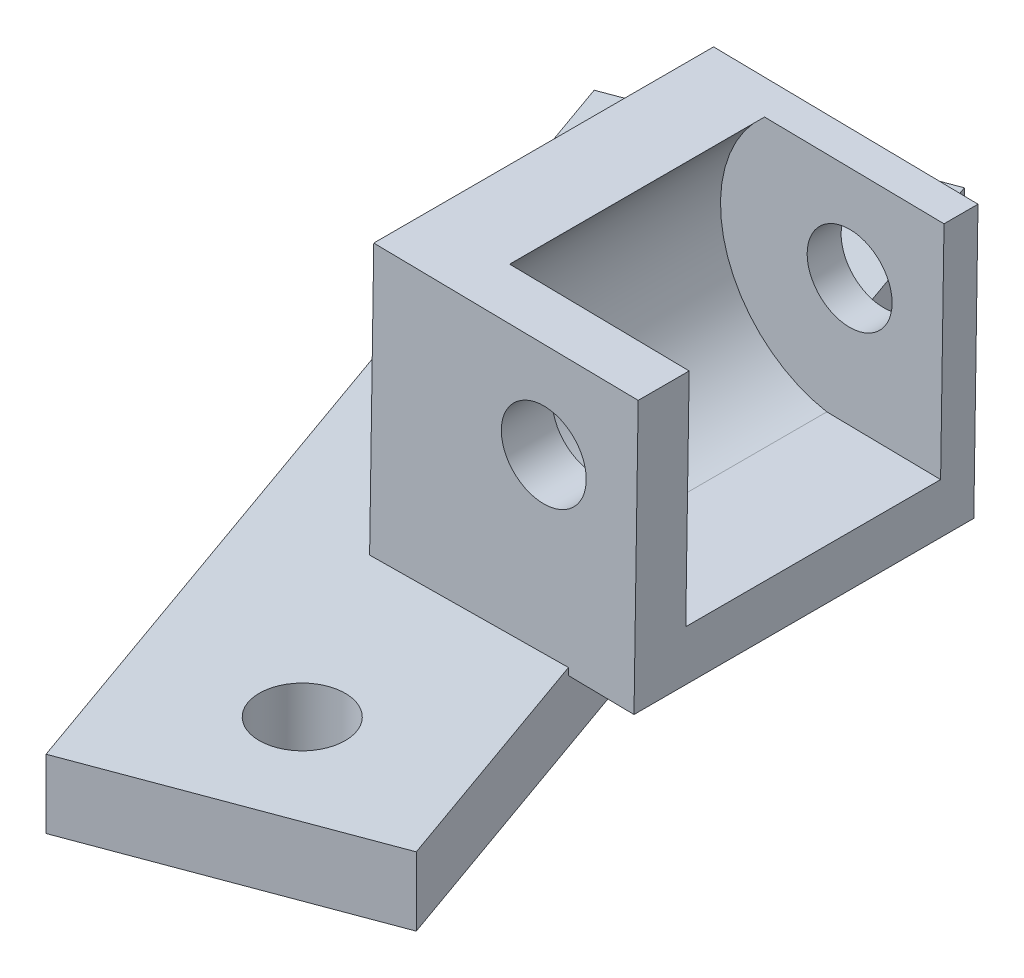
SolidWorks part; units mm, degrees
ref_plane "Front Plane" through (0, 0, 0) normal (0, 0, 1) x (1, 0, 0)
ref_plane "Top Plane" through (0, 0, 0) normal (0, 1, 0) x (1, 0, 0)
ref_plane "Right Plane" through (0, 0, 0) normal (1, 0, 0) x (0, 0, -1)
sketch "Sketch1" plane through (0, 0, 0) normal (0, 0, 1) x (1, 0, 0)
  line L0 (-620.8374, 110.7203) -> (-621.1503, 90.2249)
  line L1 (-604.7125, 110.4741) -> (-634.2525, 110.9251) construction
  line L2 (-621.1503, 90.2249) -> (-640.9147, 90.5267)
  line L3 (-640.9147, 90.5267) -> (-640.6018, 111.0221)
  line L4 (-640.6018, 111.0221) -> (-620.8374, 110.7203)
  line L5 (-606.4491, 93.8109) -> (-629.5989, 94.1643) construction
  line L6 (-606.4491, 93.8109) -> (-629.5989, 94.1643)
  arc A0 (-634.2525, 110.9251) -> (-634.4712, 96.6012) centre (-627.8931, 103.6644) ccw construction
  arc A1 (-634.4712, 96.6012) -> (-629.5989, 94.1643) centre (-627.8931, 103.6644) ccw construction
  arc A2 (-634.2525, 110.9251) -> (-634.4712, 96.6012) centre (-627.8931, 103.6644) ccw
  arc A3 (-634.4712, 96.6012) -> (-629.5989, 94.1643) centre (-627.8931, 103.6644) ccw
  dimension "D1" = 3.81
  dimension "D2" = 6.35
  dimension "D3" = 19.7667
extrude "Boss-Extrude1" add sketch "Sketch1" against normal blind 21.59 contours A3 A2 L4 L3 L2 L0 L6
sketch "Sketch2" plane through (0, 0, -19.05) normal (0, 0, -1) x (-1, 0, 0)
  line L0 (621.0921, 94.0345) -> (620.8374, 110.7203)
  line L1 (604.6203, 110.4727) -> (634.2525, 110.9251) construction
  line L2 (620.8374, 110.7203) -> (634.2525, 110.9251)
  line L3 (621.0921, 94.0345) -> (629.5989, 94.1643) construction
  line L4 (621.0921, 94.0345) -> (629.5989, 94.1643)
  line L5 (621.0921, 94.0345) -> (629.5989, 94.1643)
  circle A0 centre (627.8931, 103.6644) radius 3.175 construction
  arc A1 (629.5989, 94.1643) -> (634.2525, 110.9251) centre (627.8931, 103.6644) ccw construction
  circle A2 centre (627.8931, 103.6644) radius 3.175
  arc A3 (629.5989, 94.1643) -> (634.2525, 110.9251) centre (627.8931, 103.6644) ccw
  circle M6 centre (627.8931, 103.6644) radius 3.175
  line M7 (604.4767, 96.1432) -> (634.4712, 96.6012)
  arc M8 (634.4712, 96.6012) -> (634.2525, 110.9251) centre (627.8931, 103.6644) ccw
  line M9 (634.2525, 110.9251) -> (604.6203, 110.4727)
extrude "Boss-Extrude3" add sketch "Sketch2" along normal up to surface (2.54 mm away) contours L0 M7 M8 M9 M6 | L4 A3 L0 M7 up to face at (-632.1463, 98.2392, -21.59)
sketch "Sketch3" plane through (0, 0, 0) normal (0, 0, 1) x (1, 0, 0)
  line L0 (-640.6018, 111.0221) -> (-620.8374, 110.7203)
  line L1 (-620.8374, 110.7203) -> (-621.1503, 90.2249)
  line L2 (-621.1503, 90.2249) -> (-640.9147, 90.5267)
  line L3 (-640.9147, 90.5267) -> (-640.6018, 111.0221)
  circle A0 centre (-627.8931, 103.6644) radius 3.175
  dimension "D1" = 6.35
extrude "Boss-Extrude4" add sketch "Sketch3" along normal blind 3.81 contours L3 L0 L1 L2 | A0
ref_plane "Plane1" through (-1.0096, 97.2566, -1.0889) normal (-0.0104, 0.9999, -0.0112) x (0.9999, 0.0104, -0.0001)
sketch "Sketch4" plane through (-1.0096, 97.2566, -1.0889) normal (-0.0104, 0.9999, -0.0112) x (0.9999, 0.0104, -0.0001)
  line L0 (-662.311, 34.3361) -> (-638.8443, -30.104)
  line L5 (-638.8443, -30.104) -> (-618.5576, -22.7163)
  line L6 (-618.5576, -22.7163) -> (-642.0243, 41.7238)
  line L7 (-642.0243, 41.7238) -> (-662.311, 34.3361)
  line L8 (-620.1809, -4.8198) -> (-639.9411, -4.8232) construction
  circle A1 centre (-649.1257, 29.6766) radius 3.175
  circle A2 centre (-631.7429, -18.0568) radius 3.175
  dimension "D7" = 10.795
  dimension "D9" = 6.35
  dimension "D10" = 6.35
  dimension "D6" = 8.89
  dimension "D1" = 21.59
  dimension "D2" = 7.62
  dimension "D3" = 110
  dimension "D4" = 68.58
  dimension "D5" = 24.13
  dimension "D8" = 10.795
  dimension "D11" = 8.89
extrude "Boss-Extrude5" add sketch "Sketch4" against normal blind 5.08
